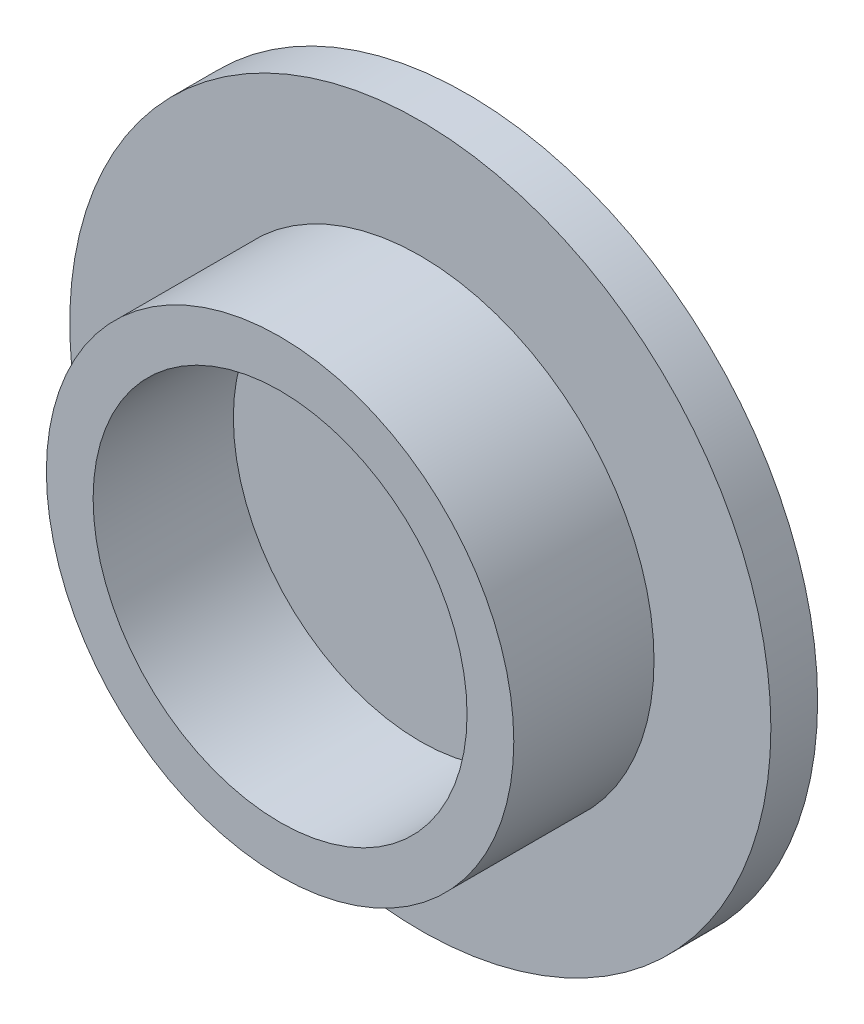
SolidWorks part; units mm, degrees
ref_plane "Front Plane" through (0, 0, 0) normal (0, 0, 1) x (1, 0, 0)
ref_plane "Top Plane" through (0, 0, 0) normal (0, 1, 0) x (1, 0, 0)
ref_plane "Right Plane" through (0, 0, 0) normal (1, 0, 0) x (0, 0, -1)
sketch "Sketch2" plane through (0, 0, 0) normal (0, 0, 1) x (1, 0, 0)
  circle A0 centre (0, 0) radius 50
  circle A1 centre (0, 0) radius 40
extrude "Boss-Extrude1" add sketch "Sketch2" along normal blind 30
sketch "Sketch3" plane through (0, 0, 0) normal (0, 0, 1) x (1, 0, 0)
  circle A0 centre (0, 0) radius 75
extrude "Boss-Extrude2" add sketch "Sketch3" against normal blind 10 separate body contours A0
